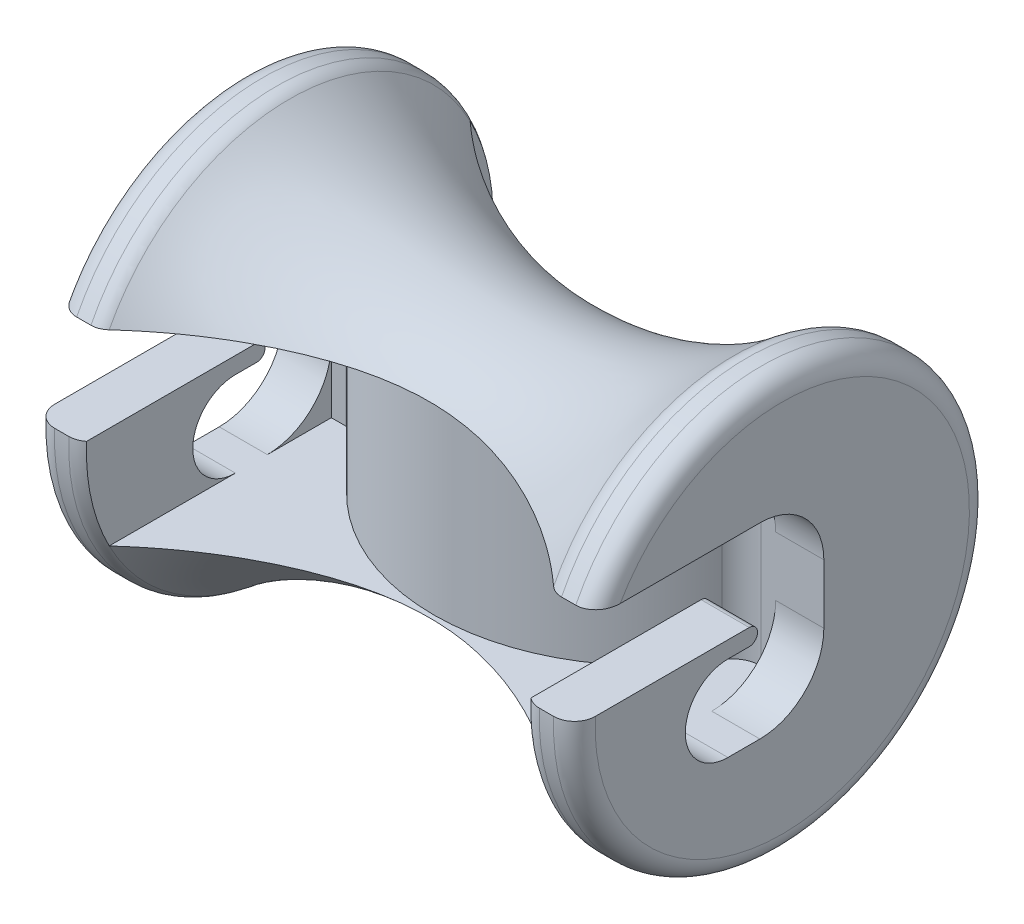
SolidWorks part; units mm, degrees
ref_plane "Front Plane" through (0, 0, 0) normal (0, 0, 1) x (1, 0, 0)
ref_plane "Top Plane" through (0, 0, 0) normal (0, 1, 0) x (1, 0, 0)
ref_plane "Right Plane" through (0, 0, 0) normal (1, 0, 0) x (0, 0, -1)
sketch "Sketch1" plane through (0, 0, 0) normal (0, 1, 0) x (1, 0, 0)
  line L0 (11.3137, 10) -> (12, 10)
  line L1 (-13, 0) -> (13, 0)
  line L2 (-13, 0) -> (-13, 9)
  line L3 (-12, 10) -> (-11.3137, 10)
  line L4 (13, 0) -> (13, 9)
  arc A1 (-10.6852, 9.7778) -> (10.6852, 9.7778) centre (0, 23) ccw
  arc A2 (-11.3137, 10) -> (-10.6852, 9.7778) centre (-11.3137, 9) cw
  arc A3 (-12, 10) -> (-13, 9) centre (-12, 9) ccw
  arc A4 (10.6852, 9.7778) -> (11.3137, 10) centre (11.3137, 9) cw
  arc A5 (13, 9) -> (12, 10) centre (12, 9) ccw
  point P5 (0, 0)
  point P8 (0, 0)
  point P9 (0, 30.6693)
  point P10 (0, 27.4686)
  point P11 (0, 0)
  point P18 (-13, 10)
  point P21 (10.9545, 10)
  point P24 (0, 0)
  dimension "D4" = 34
  dimension "D5" = 1
  dimension "D1" = 10
  dimension "D2" = 26
  dimension "D3" = 23
revolve "Revolve1" add sketch "Sketch1" angle 360 about L1
sketch "Sketch3" plane through (0, 0, 0) normal (0, 1, 0) x (1, 0, 0)
  line L1 (-9.1477, -10) -> (9.1477, -10)
  line L6 (11.3137, -10) -> (12, -10) construction
  line L8 (10.6852, -9.7778) -> (10.6852, 9.7778) construction
  line L9 (-9.9699, 2) -> (-10.6852, 2)
  line L11 (-9.1477, -10) -> (-10.6852, -10)
  line L12 (-10.6852, 2) -> (-10.6852, -10)
  line L13 (9.9699, 2) -> (10.6852, 2)
  line L15 (9.1477, -10) -> (10.6852, -10)
  line L16 (10.6852, 2) -> (10.6852, -10)
  line L17 (-10.6852, -9.7778) -> (-10.6852, 9.7778) construction
  arc A0 (-8.7869, 1.3176) -> (8.7869, 1.3176) centre (0, 6.4) ccw
  arc A1 (8.7869, 1.3176) -> (9.9699, 2) centre (9.9699, 0.6333) cw
  arc A2 (-9.9699, 2) -> (-8.7869, 1.3176) centre (-9.9699, 0.6333) cw
  point P3 (0, 0)
  point P4 (0, -10)
  point P10 (0, 0)
  point P14 (0, 0)
  point P20 (-8.2811, 2)
  point P21 (0, 0)
  point P24 (9.1477, 2)
  point P27 (-9.1477, 2)
  dimension "D4" = 1.3667
  dimension "D1" = 12
  dimension "D2" = 1.5375
  dimension "D3" = 16.4
extrude "Cut-Extrude1" cut sketch "Sketch3" against normal mid plane 9
sketch "Sketch5" plane through (-10.6852, 0, 0) normal (1, 0, 0) x (0, 0, -1)
  line L0 (2, -4.5) -> (-8.6807, -4.5) construction
  line L1 (2, -4.5) -> (2, 4.5) construction
  line L2 (2, 4.5) -> (-8.6807, 4.5) construction
  line L3 (2, -4.5) -> (-8.6807, -4.5) construction
  line L4 (2, -4.5) -> (2, 4.5) construction
  line L5 (2, 4.5) -> (-8.6807, 4.5) construction
  arc A0 (-8.6807, 4.5) -> (-8.6807, -4.5) centre (0, 0) ccw construction
  arc A1 (-8.6807, 4.5) -> (-8.6807, -4.5) centre (0, 0) ccw construction
  point P1 (-8.6807, 4.5)
sketch "Sketch6" plane through (-13, 0, 0) normal (-1, 0, 0) x (0, 0, 1)
  line L0 (-2, -4.5) -> (8.6807, -4.5) construction
  line L1 (-2, 4.5) -> (8.6807, 4.5) construction
  line L2 (-2, -4.5) -> (-2, 4.5) construction
  line L3 (1.075, -4.5) -> (2.6125, -4.5)
  line L4 (1.075, 4.5) -> (8.9303, 4.5)
  line L5 (-2, -1.425) -> (-2, 1.425)
  line L6 (1.5875, 0.4) -> (9.992, 0.4)
  line L8 (2.6125, -0.4) -> (1.5875, -0.4)
  circle A1 centre (0, 0) radius 10 construction
  arc A2 (9.992, 0.4) -> (8.9303, 4.5) centre (0, 0) ccw
  arc A3 (2.6125, -4.5) -> (2.6125, -0.4) centre (2.6125, -2.45) ccw
  arc A5 (1.075, -4.5) -> (-2, -1.425) centre (1.075, -1.425) cw
  arc A6 (1.075, 4.5) -> (-2, 1.425) centre (1.075, 1.425) ccw
  arc A7 (1.5875, -0.4) -> (1.5875, 0.4) centre (1.5875, 0) cw
  point P5 (0, 0)
  dimension "D1" = 4.1
  dimension "D2" = 3.075
  dimension "D4" = 3.075
  dimension "D3" = 4.6125
  dimension "D5" = 4.1
  dimension "D6" = 3.5875
extrude "Cut-Extrude4" cut sketch "Sketch6" against normal up to surface (2.3148 mm away) up to face at (-10.6852, 0, 3.6146)
sketch "Sketch8" plane through (13, 0, 0) normal (1, 0, 0) x (0, 0, -1)
  line L0 (-1.5875, 0.4) -> (-9.992, 0.4) construction
  line L1 (-2.6125, -0.4) -> (-1.5875, -0.4) construction
  line L2 (-1.075, -4.5) -> (-2.6125, -4.5) construction
  line L3 (2, -1.425) -> (2, 1.425) construction
  line L4 (-1.075, 4.5) -> (-8.9303, 4.5) construction
  line L5 (-1.5875, 0.4) -> (-9.992, 0.4)
  line L6 (-2.6125, -0.4) -> (-1.5875, -0.4)
  line L7 (-1.075, -4.5) -> (-2.6125, -4.5)
  line L8 (2, -1.425) -> (2, 1.425)
  line L9 (-1.075, 4.5) -> (-8.9303, 4.5)
  arc A0 (-8.9303, 4.5) -> (-9.992, 0.4) centre (0, 0) ccw construction
  arc A1 (-1.5875, -0.4) -> (-1.5875, 0.4) centre (-1.5875, 0) ccw construction
  arc A2 (-2.6125, -0.4) -> (-2.6125, -4.5) centre (-2.6125, -2.45) ccw construction
  arc A3 (-1.075, -4.5) -> (2, -1.425) centre (-1.075, -1.425) ccw construction
  arc A4 (2, 1.425) -> (-1.075, 4.5) centre (-1.075, 1.425) ccw construction
  arc A5 (-8.9303, 4.5) -> (-9.992, 0.4) centre (0, 0) ccw
  arc A6 (-1.5875, -0.4) -> (-1.5875, 0.4) centre (-1.5875, 0) ccw
  arc A7 (-2.6125, -0.4) -> (-2.6125, -4.5) centre (-2.6125, -2.45) ccw
  arc A8 (-1.075, -4.5) -> (2, -1.425) centre (-1.075, -1.425) ccw
  arc A9 (2, 1.425) -> (-1.075, 4.5) centre (-1.075, 1.425) ccw
extrude "Cut-Extrude5" cut sketch "Sketch8" against normal up to surface (2.3148 mm away) up to face at (10.6852, 0, 3.6146)
ref_plane "Plane1" through (0, 0, -3.075) normal (0, 0, 1) x (1, 0, 0)
sketch "Sketch10" plane through (0, 0, -3.075) normal (0, 0, 1) x (1, 0, 0)
  line L0 (-18.1102, 0) -> (17.0574, 0) construction
  line L1 (-10.6852, 4.51) -> (10.6852, 4.51)
  line L2 (-10.6852, 4.51) -> (-10.6852, 0.41)
  line L3 (-10.6852, 0.41) -> (10.6852, 0.41)
  line L4 (10.6852, 4.51) -> (10.6852, 0.41)
  line L5 (-10.6852, -4.5) -> (-10.6852, -1.425) construction
  line L6 (-10.6852, -4.51) -> (-10.6852, -0.41)
  line L7 (-10.6852, -0.41) -> (10.6852, -0.41)
  line L8 (10.6852, -4.51) -> (10.6852, -0.41)
  line L9 (-10.6852, -4.51) -> (10.6852, -4.51)
  point P5 (0, 0.41)
  dimension "D1" = 4.1
  dimension "D2" = 0.41
extrude "Cut-Extrude6" cut sketch "Sketch10" against normal up to next
